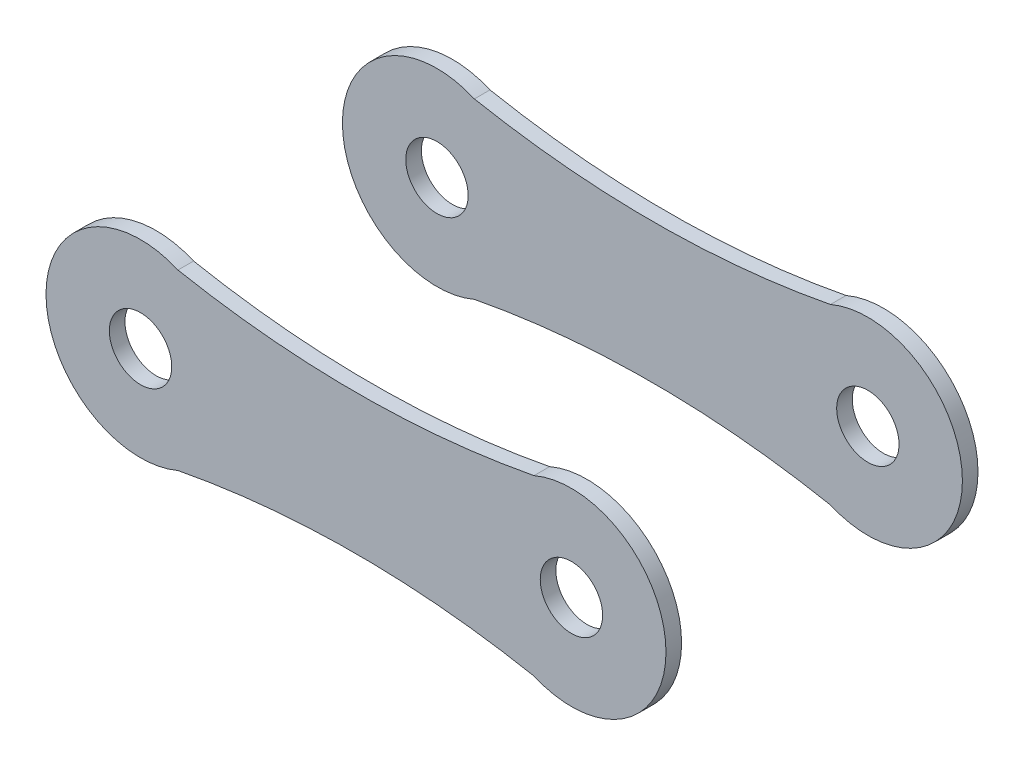
SolidWorks part; units mm, degrees
ref_plane "前视基准面" through (0, 0, 0) normal (0, 0, 1) x (1, 0, 0)
ref_plane "上视基准面" through (0, 0, 0) normal (0, 1, 0) x (1, 0, 0)
ref_plane "右视基准面" through (0, 0, 0) normal (1, 0, 0) x (0, 0, -1)
sketch "草图1" plane through (0, 0, 0) normal (0, 0, 1) x (1, 0, 0)
  line L0 (-5.584, 0) -> (20.3572, 0) construction
  arc A0 (1.1999, 2.7823) -> (1.1999, -2.7823) centre (0, 0) ccw
  arc A1 (12.6101, -2.7823) -> (12.6101, 2.7823) centre (13.81, 0) ccw
  arc A2 (1.1999, 2.7823) -> (12.6101, 2.7823) centre (6.905, 32.4276) ccw
  arc A3 (1.1999, -2.7823) -> (12.6101, -2.7823) centre (6.905, -32.4276) cw
  dimension "D1" = 6.06
  dimension "D2" = 13.81
extrude "凸台-拉伸1" add sketch "草图1" along normal blind 0.5
ref_plane "基准面1" through (0, 0, -4.5) normal (0, 0, 1) x (1, 0, 0)
ref_plane "基准面3" through (0, 0, -9) normal (0, 0, 1) x (1, 0, 0)
sketch "草图2" plane through (0, 0, -9) normal (0, 0, 1) x (1, 0, 0)
  line L0 (21.2689, 0) -> (-13.6373, 0) construction
  arc A0 (12.6101, -2.7823) -> (12.6101, 2.7823) centre (13.81, 0) ccw
  arc A1 (1.1999, 2.7823) -> (1.1999, -2.7823) centre (0, 0) ccw
  arc A2 (12.6101, 2.7823) -> (1.1999, 2.7823) centre (6.905, 32.4276) cw
  arc A3 (12.6101, -2.7823) -> (1.1999, -2.7823) centre (6.905, -32.4276) ccw
  dimension "D1" = 6.06
  dimension "D2" = 6.06
extrude "凸台-拉伸2" add sketch "草图2" against normal blind 0.5 separate body
sketch "草图3" plane through (0, 0, -9.5) normal (0, 0, -1) x (-1, 0, 0)
  circle A0 centre (-13.81, 0) radius 1
  circle A1 centre (0, 0) radius 1
extrude "切除-拉伸1" cut sketch "草图3" against normal through all both and the other way through all
